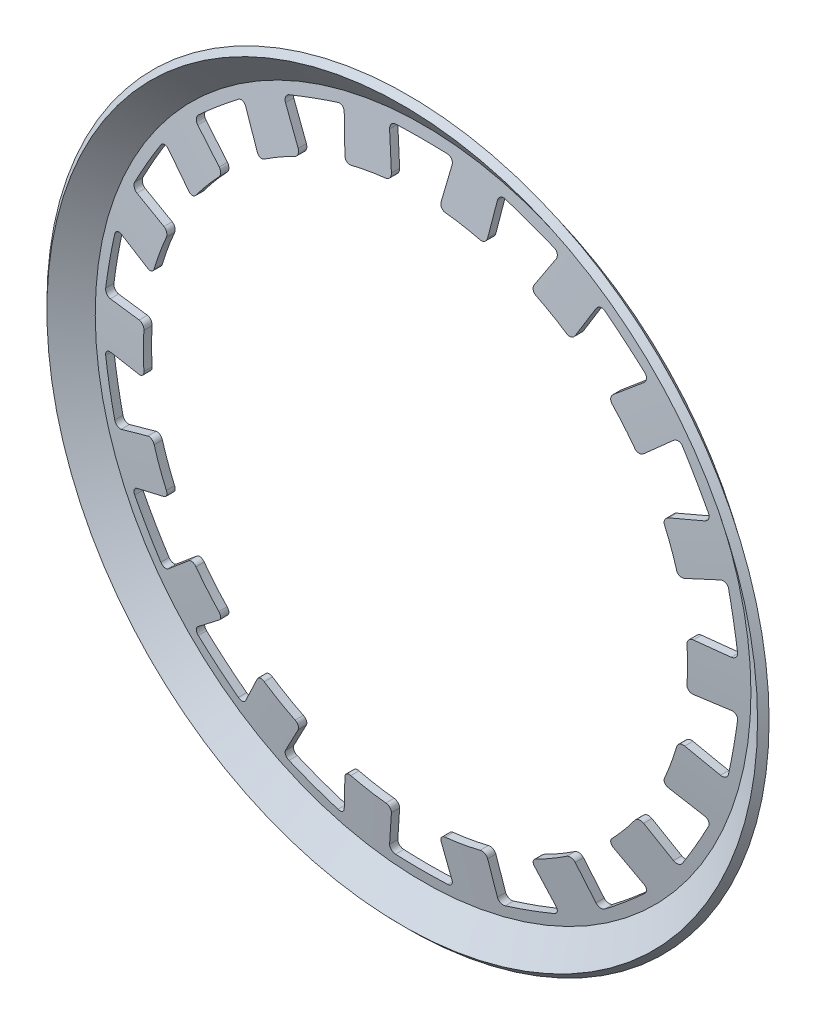
SolidWorks part; units mm, degrees
ref_plane "Front Plane" through (0, 0, 0) normal (0, 0, 1) x (1, 0, 0)
ref_plane "Top Plane" through (0, 0, 0) normal (0, 1, 0) x (1, 0, 0)
ref_plane "Right Plane" through (0, 0, 0) normal (1, 0, 0) x (0, 0, -1)
sketch "Sketch1" plane through (0, 0, 0) normal (0, 0, 1) x (1, 0, 0)
  circle A0 centre (0, 0) radius 12.7 construction
  circle A1 centre (0, 0) radius 16.8529 construction
  point P4 (-16.8529, 0)
  point P5 (-12.7, 0)
  dimension "For OD" = 25.4
  dimension "Ring OD" = 33.7058
sketch "Sketch2" plane through (0, 0, 0) normal (0, 1, 0) x (1, 0, 0)
  line L0 (16.8529, 0.6858) -> (16.8529, -0.6858) construction
  line L1 (0, 0.1905) -> (0, -0.1905) construction
  line L2 (0, 0.1905) -> (-11.7877, 0.1905) construction
  line L3 (-13.5573, 0.0485) -> (-15.3008, 0.2876) construction
  line L4 (-13.5941, 0.4381) -> (-15.4005, 0.6858) construction
  line L5 (-15.3008, 0.2876) -> (-16.5835, -0.6858) construction
  line L6 (-16.5835, -0.6858) -> (-16.8529, -0.4164) construction
  line L7 (-13.5941, 0.4381) -> (-11.7877, 0.1905) construction
  line L8 (-11.8137, -0.1905) -> (0, -0.1905) construction
  line L9 (-16.8529, -0.4164) -> (-15.4005, 0.6858) construction
  line L10 (-13.5573, 0.0485) -> (-11.8137, -0.1905) construction
  point P3 (16.8529, 0)
  point P8 (0, 0)
  dimension "Height" = 1.3716
  dimension "Ring Thickness" = 0.381
  dimension "D1" = 135
  dimension "D2" = 45
  dimension "D3" = 0.381
sketch "Sketch3" plane through (0, 0, 0) normal (0, 0, 1) x (1, 0, 0)
  line L0 (0, 0) -> (0, 14.7828) construction
  line L1 (0, 0) -> (2.2053, 12.5071) construction
  line L2 (0, 0) -> (-2.2053, 12.5071) construction
  line L3 (1.1069, 12.6517) -> (1.5136, 14.744) construction
  line L4 (-1.5136, 14.744) -> (1.5136, 14.744) construction
  line L5 (-1.5136, 14.744) -> (-1.1069, 12.6517) construction
  line L6 (-1.1069, 12.6517) -> (0, 12.7) construction
  line L7 (-1.1069, 12.6517) -> (-2.2053, 12.5071) construction
  circle A1 centre (0, 0) radius 14.7828 construction
  circle A3 centre (0, 0) radius 12.7 construction
  arc A4 (-1.5136, 14.744) -> (1.5136, 14.744) centre (0, -14.7828) cw construction
  point P4 (0, 14.7828)
  point P20 (0, 14.744)
  point P36 (0, 14.7828)
  dimension "D1" = 1
  dimension "D2" = 29.5656
  dimension "Angle" = 20
sketch "Sketch4" plane through (0, 0, 0) normal (0, 1, 0) x (1, 0, 0)
  line L0 (-16.8529, -0.4164) -> (-16.5835, -0.6858)
  line L1 (-16.5835, -0.6858) -> (-15.3008, 0.2876)
  line L2 (-15.3008, 0.2876) -> (-11.8137, -0.1905)
  line L3 (-11.8137, -0.1905) -> (0, -0.1905)
  line L4 (0, -0.1905) -> (0, 0.1905)
  line L5 (0, 0.1905) -> (-11.7877, 0.1905)
  line L6 (-11.7877, 0.1905) -> (-15.4005, 0.6858)
  line L7 (-15.4005, 0.6858) -> (-16.8529, -0.4164)
revolve "Revolve1" add sketch "Sketch4" angle 360 about L4
sketch "Sketch5" plane through (0, 0, 0) normal (0, 0, 1) x (1, 0, 0)
  line L0 (-1.5136, 14.744) -> (-1.1069, 12.6517)
  line L1 (1.5136, 14.744) -> (1.1069, 12.6517)
  line L2 (-2.2053, 12.5071) -> (0, 0)
  line L3 (2.2053, 12.5071) -> (0, 0)
  arc A0 (-1.5136, 14.744) -> (1.5136, 14.744) centre (0, -14.7828) cw
  arc A1 (1.5136, 14.744) -> (-1.5136, 14.744) centre (0, -14.7828) ccw construction
  arc A2 (-2.2053, 12.5071) -> (-1.1069, 12.6517) centre (0, 0) cw
  circle A3 centre (0, 0) radius 12.7 construction
  arc A4 (1.1069, 12.6517) -> (2.2053, 12.5071) centre (0, 0) cw
extrude "Cut-Extrude1" cut sketch "Sketch5" along normal through all both and the other way through all
fillet "Fillet1" radius 0.254 4 edges at (1.1069, 12.6517, -0.1233) (-1.1069, 12.6517, -0.1233) (1.5136, 14.744, -0.4141) (-1.5136, 14.744, -0.4141)
pattern_circular "CirPattern1" count 18 over 360 about axis through (0, 0, 0) along (0, 0, 1) of "Cut-Extrude1", "Fillet1"
equation "\"D3@Sketch2\"=\"Ring Thickness@Sketch2\""
